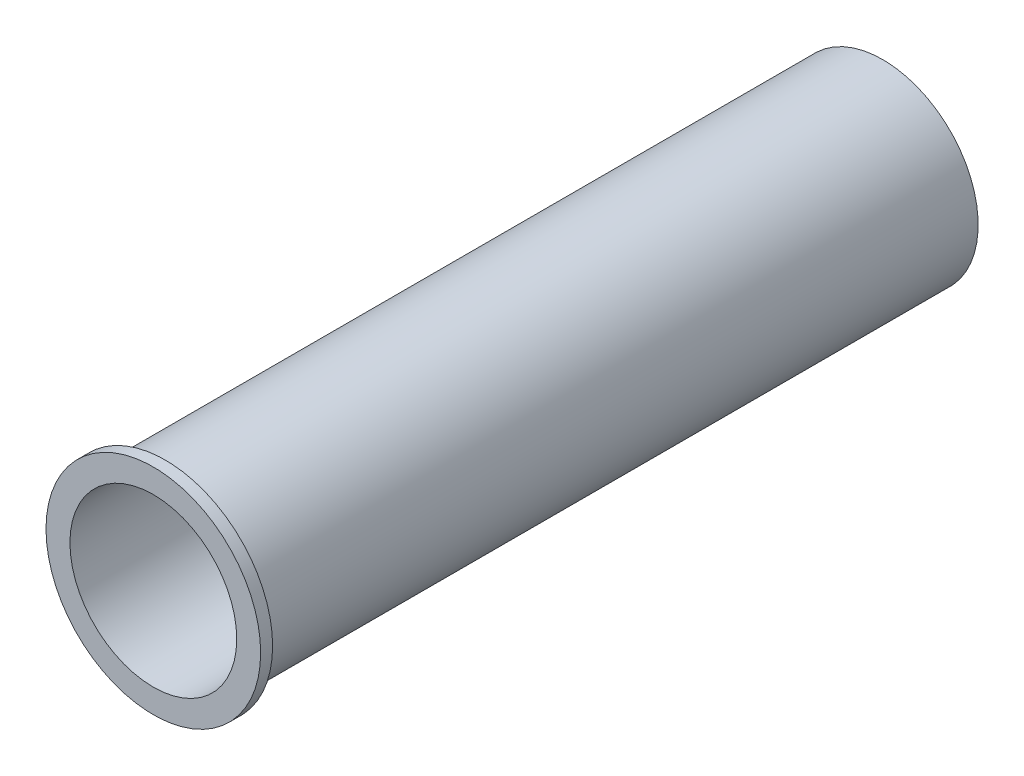
SolidWorks part; units mm, degrees
ref_plane "Alzado" through (0, 0, 0) normal (1, 0, 0) x (0, 1, 0)
ref_plane "Planta" through (0, 0, 0) normal (0, 0, 1) x (0, 1, 0)
ref_plane "Vista lateral" through (0, 0, 0) normal (0, 1, 0) x (-1, 0, 0)
sketch "Croquis1" plane through (0, 0, 0) normal (1, 0, 0) x (0, 1, 0)
  line L0 (13.95, -60) -> (13.95, 60)
  line L1 (13.95, 60) -> (17.95, 60)
  line L2 (17.95, 60) -> (17.95, 58)
  line L3 (17.95, 58) -> (15.95, 58)
  line L4 (15.95, 58) -> (15.95, -62)
  line L5 (15.95, -62) -> (12.45, -62)
  line L6 (12.45, -62) -> (12.45, -60)
  line L7 (12.45, -60) -> (13.95, -60)
  line L8 (0, 0) -> (0, 4.1277) construction
  point P3 (13.95, 0)
  dimension "D1" = 2
  dimension "D2" = 1.5
  dimension "D3" = 2
  dimension "D4" = 2
  dimension "D5" = 2
  dimension "D7" = 120
  dimension "D6" = 27.9
revolve "Revolución1" add sketch "Croquis1" angle 360 about L8
equation "\"D4@Croquis1\"=\"D3@Croquis1\""
equation "\"D5@Croquis1\"=\"D3@Croquis1\""
